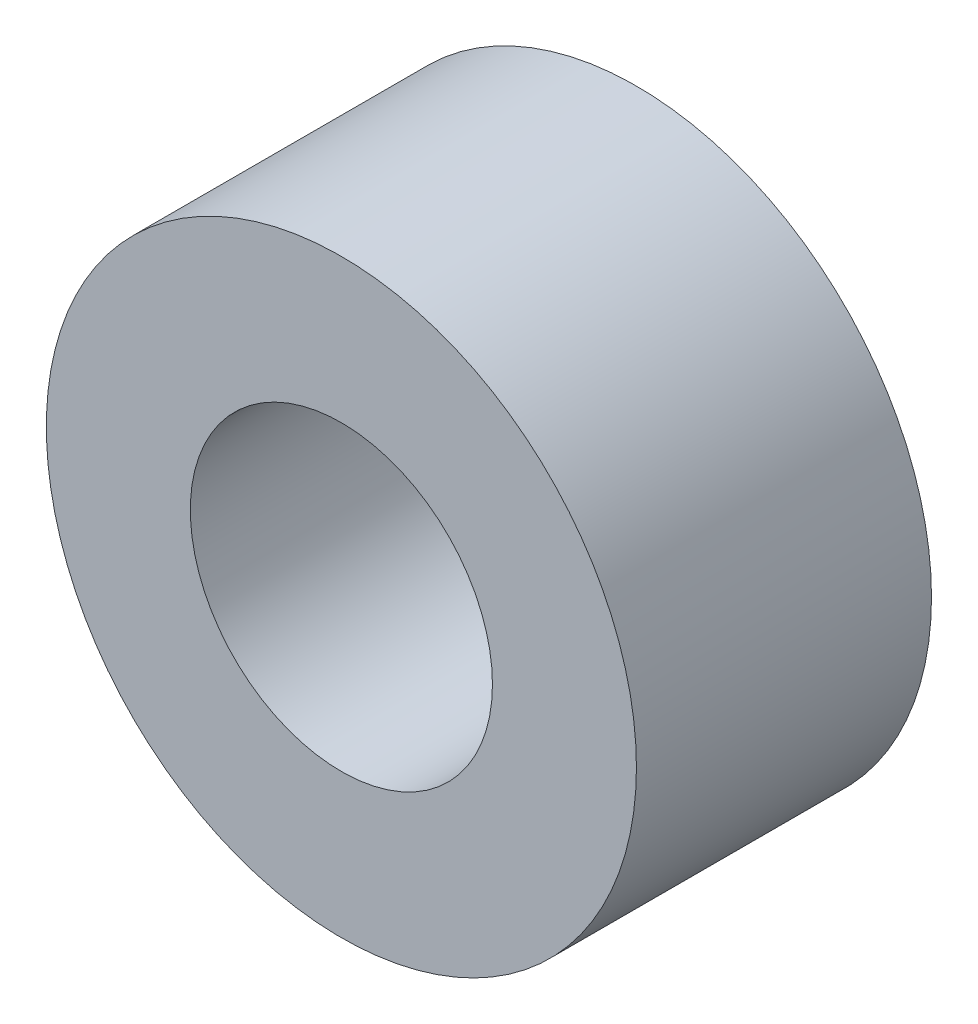
SolidWorks part; units mm, degrees
ref_plane "Front Plane" through (0, 0, 0) normal (0, 0, 1) x (1, 0, 0)
ref_plane "Top Plane" through (0, 0, 0) normal (0, 1, 0) x (1, 0, 0)
ref_plane "Right Plane" through (0, 0, 0) normal (1, 0, 0) x (0, 0, -1)
sketch "Sketch1" plane through (0, 0, 0) normal (0, 0, 1) x (1, 0, 0)
  circle A0 centre (0, 0) radius 1.5875
  circle A1 centre (0, 0) radius 0.8128
  dimension "OD" = 3.175
  dimension "ID" = 1.6256
extrude "Extrude1" add sketch "Sketch1" along normal mid plane 1.5875
sketch "Sketch2" plane through (0, 0, 0) normal (1, 0, 0) x (0, 0, -1)
  line L0 (-0.7937, -0.8128) -> (0.7937, -0.8128) construction
  line L3 (0.7937, 0.8128) -> (-0.7937, 0.8128) construction
  line L5 (-0.7937, -0.8128) -> (0.7937, -0.8128)
  line L6 (0.7937, 0.8128) -> (-0.7937, 0.8128)
sketch "Sketch4" plane through (0, 0, 0.7937) normal (0, 0, 1) x (1, 0, 0)
  line L0 (0, 0) -> (-0.5747, 0.5747)
  line L1 (0, -2.1828) -> (0, 2.1828) construction
  circle A0 centre (0, 0) radius 0.8128 construction
  dimension "D1" = 45
